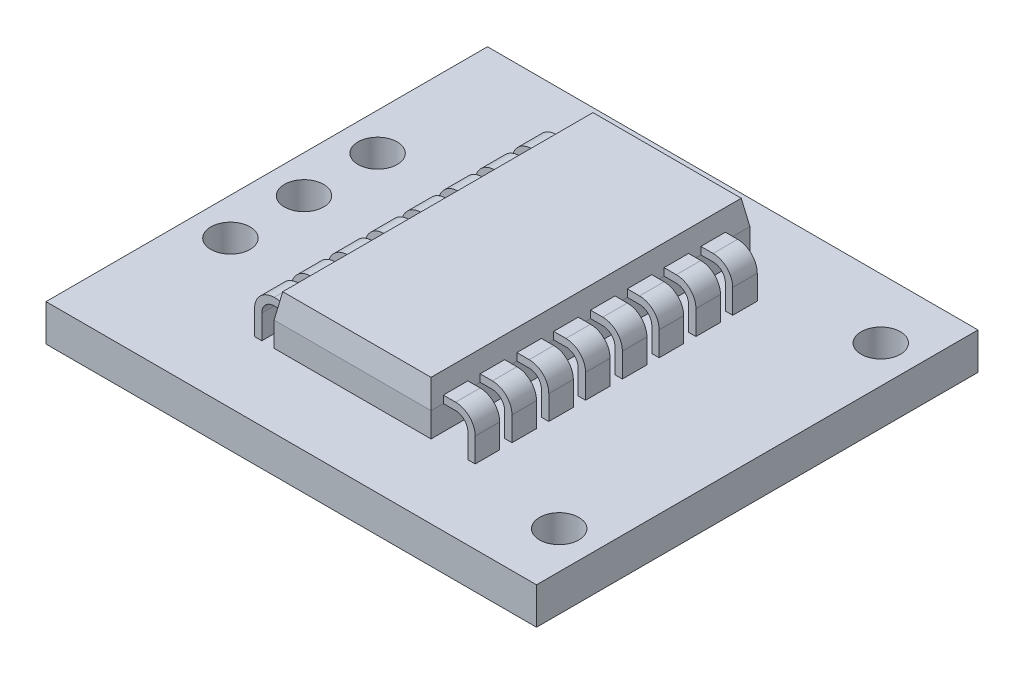
SolidWorks part; units mm, degrees
ref_plane "Front Plane" through (0, 0, 0) normal (0, 0, 1) x (1, 0, 0)
ref_plane "Top Plane" through (0, 0, 0) normal (0, 1, 0) x (1, 0, 0)
ref_plane "Right Plane" through (0, 0, 0) normal (1, 0, 0) x (0, 0, -1)
sketch "Sketch1" plane through (0, 0, 0) normal (0, 1, 0) x (1, 0, 0)
  line L1 (-5, 4.5) -> (5, 4.5)
  line L2 (-5, 4.5) -> (-5, -4.5)
  line L3 (-5, -4.5) -> (5, -4.5)
  line L4 (5, 4.5) -> (5, -4.5)
  line L5 (-5, 4.5) -> (5, -4.5) construction
  line L6 (-5, -4.5) -> (5, 4.5) construction
  circle A0 centre (-4.24, 0) radius 0.4
  circle A1 centre (-4.24, 1.5) radius 0.4
  circle A2 centre (-4.24, -1.5) radius 0.4
  circle A3 centre (4.24, 3.2779) radius 0.4
  circle A4 centre (4.24, -3.2779) radius 0.4
  point P0 (0, 0)
  dimension "D3" = 0.8
  dimension "D1" = 10
  dimension "D2" = 9
  dimension "D4" = 0.76
  dimension "D5" = 1.5
  dimension "D6" = 1.5
  dimension "D7" = 0.76
extrude "Boss-Extrude1" add sketch "Sketch1" along normal blind 0.75
sketch "Sketch2" plane through (0, 0.75, 0) normal (0, 1, 0) x (1, 0, 0)
  line L1 (-1.6, 3.25) -> (1.6, 3.25)
  line L2 (-1.6, 3.25) -> (-1.6, -3.25)
  line L3 (-1.6, -3.25) -> (1.6, -3.25)
  line L4 (1.6, 3.25) -> (1.6, -3.25)
  line L5 (-1.6, 3.25) -> (1.6, -3.25) construction
  line L6 (-1.6, -3.25) -> (1.6, 3.25) construction
  point P0 (0, 0)
  dimension "D1" = 6.5
  dimension "D2" = 3.2
extrude "Boss-Extrude2" add sketch "Sketch2" along normal blind 0.5 draft 10 and the other way blind 0.5 from offset 0.75 separate body
sketch "Sketch3" plane through (0, 0, 3.25) normal (0, 0, 1) x (1, 0, 0)
  line L0 (-1.6, 1.5) -> (-1.85, 1.5)
  line L1 (-2.1, 1.25) -> (-2.1, 0.7579)
  arc A0 (-1.85, 1.5) -> (-2.1, 1.25) centre (-1.85, 1.25) ccw
  point P6 (-2.1, 1.5)
  dimension "D2" = 0.25
  dimension "D1" = 0.5
extrude "Extrude-Thin1" add sketch "Sketch3" along normal blind 0.5 from offset 0.75 separate body thin offset against normal yes
pattern_linear "LPattern1" count 8 spacing 0.75 along (0, 0, -1) of "Extrude-Thin1"
mirror "Mirror1" about plane through (0, 0, 0) normal (1, 0, 0) of bodies 103 104 105 106 107 108 109 110
